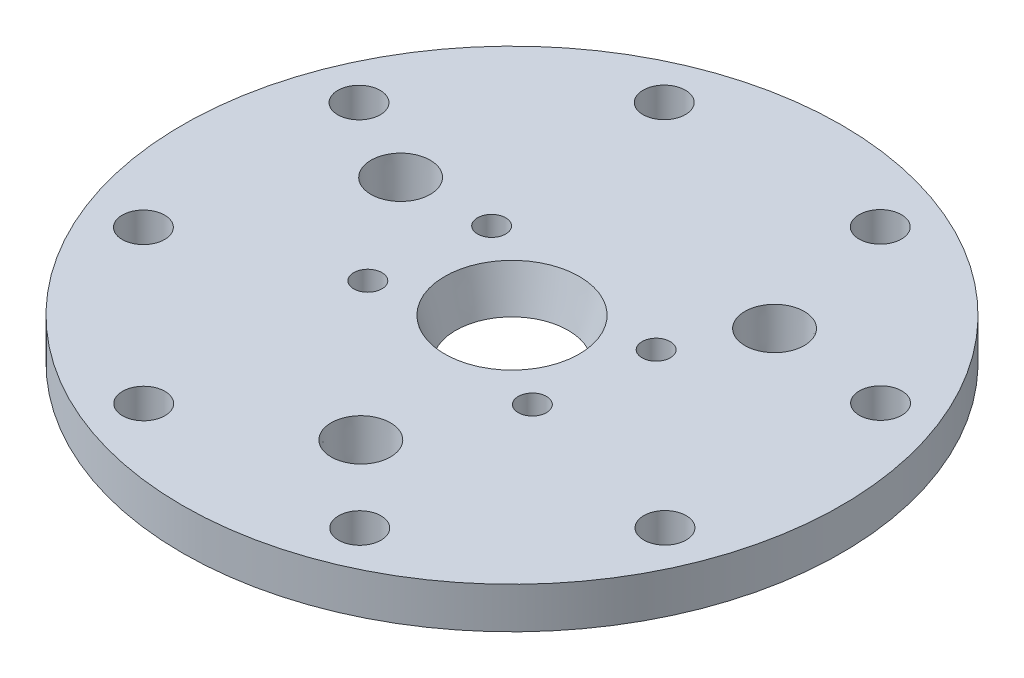
SolidWorks part; units mm, degrees
material "AISI 1020"
ref_plane "Front Plane" through (0, 0, 0) normal (0, 0, 1) x (1, 0, 0)
ref_plane "Top Plane" through (0, 0, 0) normal (0, 1, 0) x (1, 0, 0)
ref_plane "Right Plane" through (0, 0, 0) normal (1, 0, 0) x (0, 0, -1)
sketch "Sketch1" plane through (0, 0, 0) normal (0, 1, 0) x (1, 0, 0)
  circle A0 centre (0, 0) radius 76.2
  dimension "D1" = 152.4
extrude "Boss-Extrude1" add sketch "Sketch1" along normal blind 9.525 contours A0
sketch "Sketch5" plane through (0, 0, 0) normal (0, 0, 1) x (1, 0, 0)
  line L0 (0, 0) -> (0, 29.9809) construction
  line L1 (0, 0) -> (0, 9.525)
  line L2 (13, 0) -> (15.5522, 9.525)
  line L4 (76.2, 9.525) -> (-76.2, 9.525) construction
  line L6 (-76.2, 0) -> (76.2, 0) construction
  line L7 (0, 0) -> (13, 0)
  line L8 (15.5522, 9.525) -> (0, 9.525)
  line L9 (13, 0) -> (13, 9.525) construction
  dimension "D1" = 13
  dimension "D3" = 15
revolve "Cut-Revolve1" cut sketch "Sketch5" angle 360 about L0
sketch "Sketch6" plane through (0, 0, 0) normal (0, 1, 0) x (1, 0, 0)
  line L0 (0, 0) -> (46.194, 19.1342) construction
  line L1 (0, 0) -> (76.2, 0) construction
  circle A0 centre (46.194, 19.1342) radius 2.75
  circle A1 centre (0, 0) radius 76.2 construction
  dimension "D1" = 5.5
  dimension "D2" = 50
  dimension "D3" = 22.5
extrude "Cut-Extrude3" [suppressed] cut sketch "Sketch6" along normal through all
pattern_circular "CirPattern1" [suppressed] count 8 over 360
sketch "fuel-nipple-clearance" plane through (0, 9.525, 0) normal (0, 1, 0) x (1, 0, 0)
  line L0 (0, 0) -> (33.0117, 27.7001) construction
  line L1 (0, 0) -> (54.5383, 0) construction
  circle A0 centre (33.0117, 27.7001) radius 6.35
  circle A1 centre (0, 0) radius 55 construction
  circle A2 centre (33.0117, 27.7001) radius 11.9062 construction
  circle A3 centre (0, 0) radius 31.1875 construction
  dimension "D1" = 12.7
  dimension "D4" = 110
  dimension "D5" = 23.8125
  dimension "D3" = 40
sketch "Sketch8" plane through (0, 9.525, 0) normal (0, 1, 0) x (1, 0, 0)
  line L0 (0, 0) -> (17.5, 0) construction
  dimension "D1" = 17.5
sketch "Sketch9" plane through (0, 9.525, 0) normal (0, 1, 0) x (1, 0, 0)
  circle A0 centre (0, 0) radius 65.2 construction
  dimension "D1" = 130.4
hole_wizard "3/8 (0.375) Diameter Hole1" [suppressed] positions "Sketch10" profile "Sketch11" hole size "3/8" standard "ANSI Inch"
sketch "Sketch10" plane through (0, 10, 0) normal (0, 1, 0) x (1, 0, 0)
  circle A0 centre (0, 0) radius 65.2 construction
  point P0 (-65.2, 0)
sketch "Sketch11" plane through (-65.2, 10, 0) normal (1, 0, 0) x (0, 0, 1)
  line L0 (0, 0) -> (0, 10)
  line L1 (0, 10) -> (4.7625, 10)
  line L2 (4.7625, 10) -> (4.7625, 0)
  line L5 (4.7625, 0) -> (0, 0)
  line L11 (0, -6.35) -> (0, 107.95) construction
  dimension "Thru Hole Dia." = 9.525
  dimension "Thru Hole Depth" = 10
pattern_circular "CirPattern4" [suppressed] count 8 over 360
hole_wizard "Tap Drill for M4x0.7 Tap1" [suppressed] positions "Sketch12" profile "Sketch13" hole size "M4x0.7" standard "ANSI Metric"
sketch "Sketch12" plane through (0, 10, 0) normal (0, 1, 0) x (1, 0, 0)
  point P0 (17.5, 0)
sketch "Sketch13" plane through (17.5, 10, 0) normal (1, 0, 0) x (0, 0, 1)
  line L0 (0, 0) -> (0, 8.9914)
  line L1 (0, 8.9914) -> (1.65, 8)
  line L2 (1.65, 8) -> (1.65, 0)
  line L5 (1.65, 0) -> (0, 0)
  line L10 (0, 8.9914) -> (-1.65, 8) construction
  line L11 (0, -6.35) -> (0, 107.95) construction
  dimension "Hole Dia." = 3.3
  dimension "Hole Depth" = 8
  dimension "Drill Angle" = 118
cosmetic thread "Cosmetic Thread5" [suppressed] parameters "D2"=4.1656
pattern_circular "CirPattern5" [suppressed] count 6 over 360
cosmetic thread "Cosmetic Thread6" [suppressed] parameters "D2"=4.1656
cosmetic thread "Cosmetic Thread7" [suppressed] parameters "D2"=4.1656
cosmetic thread "Cosmetic Thread8" [suppressed] parameters "D2"=4.1656
cosmetic thread "Cosmetic Thread9" [suppressed] parameters "D2"=4.1656
cosmetic thread "Cosmetic Thread10" [suppressed] parameters "D2"=4.1656
hole_wizard "1/4 NPT Tapped Hole1" positions "Sketch14" profile "Sketch15" size "1/4" standard "ANSI Inch" end condition through all
sketch "Sketch14" plane through (0, 9.525, 0) normal (0, 1, 0) x (1, 0, 0)
  point P0 (33.0117, 27.7001)
sketch "Sketch15" plane through (33.0117, 9.525, -27.7001) normal (1, 0, 0) x (0, 0, 1)
  line L0 (0, 0) -> (0, 9.525)
  line L1 (0, 9.525) -> (5.5626, 9.525)
  line L2 (-6.558, 10.0203) -> (-6.858, 0) construction
  line L3 (5.5626, 9.525) -> (5.5626, 10.0203)
  line L4 (5.5626, 10.0203) -> (6.558, 10.0203)
  line L5 (6.558, 10.0203) -> (6.858, 0)
  line L7 (6.858, 0) -> (0, 0)
  line L8 (0, -6.35) -> (0, 107.95) construction
  line L11 (-5.5626, 10.0203) -> (-6.558, 10.0203) construction
  dimension "Thru Tap Drill Dia." = 11.1252
  dimension "Thru Tap Drill Depth" = 9.525
  dimension "Thread Dia." = 13.716
  dimension "Thread Angle" = 3.43
  dimension "Thread Depth" = 10.0203
pattern_circular "CirPattern6" count 3 over 360 about axis through (0, 0, 0) along (0, 1, 0) of "1/4 NPT Tapped Hole1"
hole_wizard "3/8 Clearance Hole1" positions "Sketch16" profile "Sketch17" hole size "3/8" standard "ANSI Inch" end condition through all
sketch "Sketch16" plane through (0, 9.525, 0) normal (0, 1, 0) x (1, 0, 0)
  line L0 (60.208, 25.0136) -> (60.2072, 25.0136) construction
  line L1 (60.2581, -24.8888) -> (60.2574, -24.8885) construction
  line L2 (24.8862, 60.2645) -> (24.8856, 60.2643) construction
  line L3 (-25.0162, 60.2143) -> (-25.0165, 60.2141) construction
  line L4 (-60.2169, -25.0099) -> (-60.2169, -25.0096) construction
  line L5 (-24.8951, -60.2608) -> (-24.8954, -60.2602) construction
  point P0 (60.2072, 25.0136)
  point P4 (60.2574, -24.8885)
  point P8 (24.8856, 60.2643)
  point P12 (-25.0165, 60.2141)
  point P16 (-60.2671, 24.8925)
  point P19 (-60.2169, -25.0096)
  point P23 (-24.8954, -60.2602)
  point P27 (25.0067, -60.2101)
sketch "Sketch17" plane through (60.2072, 9.525, -25.0136) normal (1, 0, 0) x (0, 0, 1)
  line L0 (0, 0) -> (0, 9.525)
  line L1 (0, 9.525) -> (4.9022, 9.525)
  line L2 (4.9022, 9.525) -> (4.9022, 0)
  line L5 (4.9022, 0) -> (0, 0)
  line L11 (0, -6.35) -> (0, 107.95) construction
  dimension "Thru Hole Dia." = 9.8044
  dimension "Thru Hole Depth" = 9.525
hole_wizard "1/4 Clearance Hole1" positions "Sketch18" profile "Sketch19" hole size "1/4" standard "ANSI Inch" end condition through all
sketch "Sketch18" plane through (0, 9.525, 0) normal (0, 1, 0) x (1, 0, 0)
  point P3 (-20.2404, 15.531)
  point P8 (20.2404, -15.531)
  point P13 (-23.5705, -9.7632)
  point P22 (23.5705, 9.7632)
  point P26 (0, 0)
  point P27 (0, 0)
sketch "Sketch19" plane through (-20.2404, 9.525, -15.531) normal (1, 0, 0) x (0, 0, 1)
  line L0 (0, 0) -> (0, 9.525)
  line L1 (0, 9.525) -> (3.2639, 9.525)
  line L2 (3.2639, 9.525) -> (3.2639, 0)
  line L5 (3.2639, 0) -> (0, 0)
  line L11 (0, -6.35) -> (0, 107.95) construction
  dimension "Thru Hole Dia." = 6.5278
  dimension "Thru Hole Depth" = 9.525
